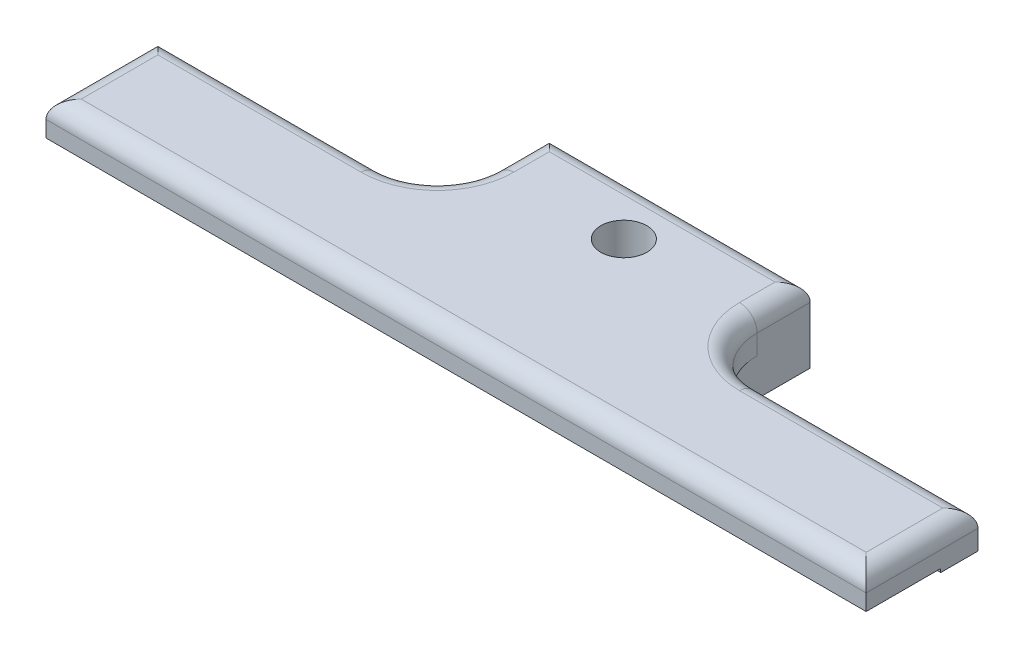
SolidWorks part; units mm, degrees
ref_plane "Front Plane" through (0, 0, 0) normal (0, 0, 1) x (1, 0, 0)
ref_plane "Top Plane" through (0, 0, 0) normal (0, 1, 0) x (1, 0, 0)
ref_plane "Right Plane" through (0, 0, 0) normal (1, 0, 0) x (0, 0, -1)
sketch "Sketch1" plane through (0, 0, 0) normal (0, 1, 0) x (1, 0, 0)
  line L0 (22.225, -9.525) -> (69.85, -9.525)
  line L2 (-22.225, -9.525) -> (-22.225, 9.525)
  line L3 (-22.225, 9.525) -> (22.225, 9.525)
  line L4 (22.225, -9.525) -> (22.225, 9.525)
  line L5 (-22.225, -9.525) -> (22.225, 9.525) construction
  line L6 (-22.225, 9.525) -> (22.225, -9.525) construction
  line L7 (-69.85, -28.575) -> (69.85, -28.575)
  line L8 (-69.85, -28.575) -> (-69.85, -9.525)
  line L9 (-69.85, -9.525) -> (-22.225, -9.525)
  line L10 (69.85, -28.575) -> (69.85, -9.525)
  line L11 (-69.85, -28.575) -> (69.85, -9.525) construction
  line L12 (-69.85, -9.525) -> (69.85, -28.575) construction
  line L13 (-69.85, -15.875) -> (69.85, -15.875) construction
  line L14 (-19.1262, 9.525) -> (-19.1262, -9.525) construction
  line L15 (-19.1262, -9.525) -> (-22.225, -9.525) construction
  line L16 (0, 0) -> (0, -28.575) construction
  circle A0 centre (0, 0) radius 3.925
  circle A1 centre (0, 0) radius 8.89
  point P7 (0, -19.05)
  dimension "D1" = 7.85
  dimension "D4" = 17.78
  dimension "D2" = 44.45
  dimension "D3" = 139.7
  dimension "D5" = 19.05
  dimension "D6" = 19.05
  dimension "D8" = 19.1262
  dimension "D7" = 12.7
extrude "Boss-Extrude1" add sketch "Sketch1" along normal blind 6.35 contours A1 A0 | L7 L10 L0 L4 L3 L2 L9 L8 A1
sketch "Sketch2" plane through (69.85, 0, 0) normal (1, 0, 0) x (0, 0, -1)
  line L0 (-15.875, 0) -> (-15.875, 0.6)
  line L1 (-15.875, 0.6) -> (-28.575, 0.6)
  line L2 (-28.575, 6.35) -> (-28.575, 0) construction
  line L3 (-28.575, 0) -> (-9.525, 0) construction
  line L4 (-28.575, 0.6) -> (-28.575, 0)
  line L5 (-28.575, 0) -> (-15.875, 0)
  dimension "D1" = 0.6
extrude "Cut-Extrude1" cut sketch "Sketch2" against normal through all
sketch "Sketch3" plane through (0, 0, 0) normal (0, -1, 0) x (1, 0, 0)
  line L0 (-22.225, -9.525) -> (22.225, -9.525) construction
  line L1 (-22.225, 9.525) -> (-22.225, -9.525) construction
  line L2 (-19.1262, 9.525) -> (-22.225, 9.525) construction
  line L3 (-19.1262, -9.525) -> (-19.1262, 9.525) construction
  line L4 (-22.225, -9.525) -> (-19.1262, -9.525)
  line L5 (-22.225, 9.525) -> (-22.225, -9.525)
  line L6 (-19.1262, 9.525) -> (-22.225, 9.525)
  line L7 (-19.1262, -9.525) -> (-19.1262, 9.525)
extrude "Boss-Extrude2" add sketch "Sketch3" along normal blind 6.35
mirror "Mirror1" about plane through (0, 0, 0) normal (1, 0, 0) of "Boss-Extrude2"
fillet "Fillet4" radius 10 2 edges at (22.225, 3.175, 9.525) (-22.225, 3.175, 9.525)
fillet "Fillet1" radius 3 10 edges at (0, 6.35, -9.525) (51.0375, 6.35, 9.525) (22.225, 6.35, -5) (-22.225, 6.35, -5) (-51.0375, 6.35, 9.525) (-69.85, 6.35, 19.05) (69.85, 6.35, 19.05) (0, 6.35, 28.575) (25.1539, 6.35, 6.5961) (-25.1539, 6.35, 6.5961)
fillet "Fillet2" radius 1 2 edges at (-19.1262, 0, 0) (19.1262, 0, 0)
